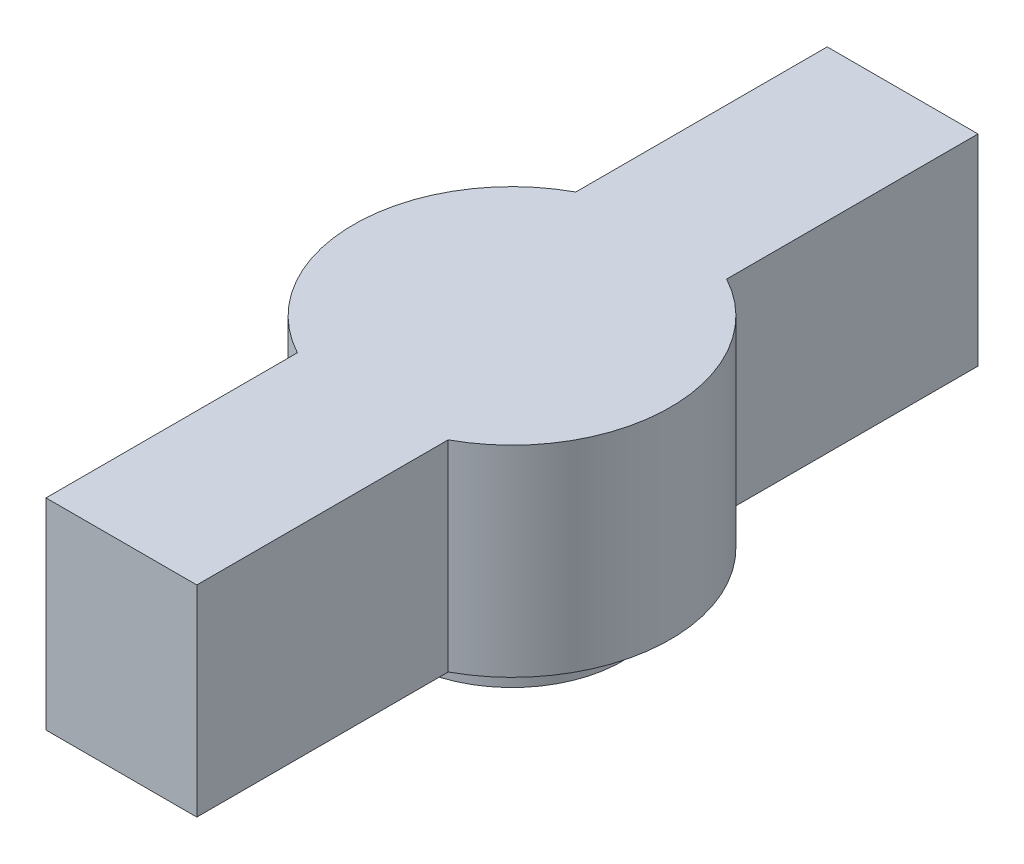
SolidWorks part; units mm, degrees
material "Alloy Steel"
ref_plane "Front Plane" through (0, 0, 0) normal (0, 0, 1) x (1, 0, 0)
ref_plane "Top Plane" through (0, 0, 0) normal (0, 1, 0) x (1, 0, 0)
ref_plane "Right Plane" through (0, 0, 0) normal (1, 0, 0) x (0, 0, -1)
sketch "Sketch1" plane through (0, 0, 0) normal (0, 1, 0) x (1, 0, 0)
  line L0 (-1.27, 6.4807) -> (-1.27, 11.5607)
  line L1 (-1.27, 11.5607) -> (1.27, 11.5607)
  line L2 (1.27, 11.5607) -> (1.27, 6.4807)
  line L3 (-6.0373, 0) -> (8.2381, 0) construction
  line L4 (1.27, -11.5607) -> (1.27, -6.4807)
  line L5 (-1.27, -11.5607) -> (1.27, -11.5607)
  line L6 (-1.27, -6.4807) -> (-1.27, -11.5607)
  circle A0 centre (0, 0) radius 6.604
  dimension "D2" = 13.208
  dimension "D1" = 5.08
  dimension "D3" = 2.54
extrude "Boss-Extrude1" add sketch "Sketch1" along normal blind 2.54 contours A0 L6 L5 L4 | L3 A0 | A0 L3 | A0 L2 L1 L0
sketch "Sketch2" plane through (0, 2.54, 0) normal (0, 1, 0) x (1, 0, 0)
  line L0 (-13.4608, 0) -> (16.2321, 0) construction
  line L1 (-4.5, 8.3098) -> (-4.5, 23.3098)
  line L2 (-4.5, 23.3098) -> (4.5, 23.3098)
  line L3 (4.5, 23.3098) -> (4.5, 8.3098)
  line L4 (4.5, -23.3098) -> (4.5, -8.3098)
  line L5 (-4.5, -23.3098) -> (4.5, -23.3098)
  line L6 (-4.5, -8.3098) -> (-4.5, -23.3098)
  arc A0 (-4.5, 8.3098) -> (-4.5, -8.3098) centre (0, 0) ccw
  arc A1 (4.5, -8.3098) -> (4.5, 8.3098) centre (0, 0) ccw
  dimension "D1" = 18.9
  dimension "D2" = 15
  dimension "D3" = 9
extrude "Boss-Extrude2" add sketch "Sketch2" along normal blind 12
